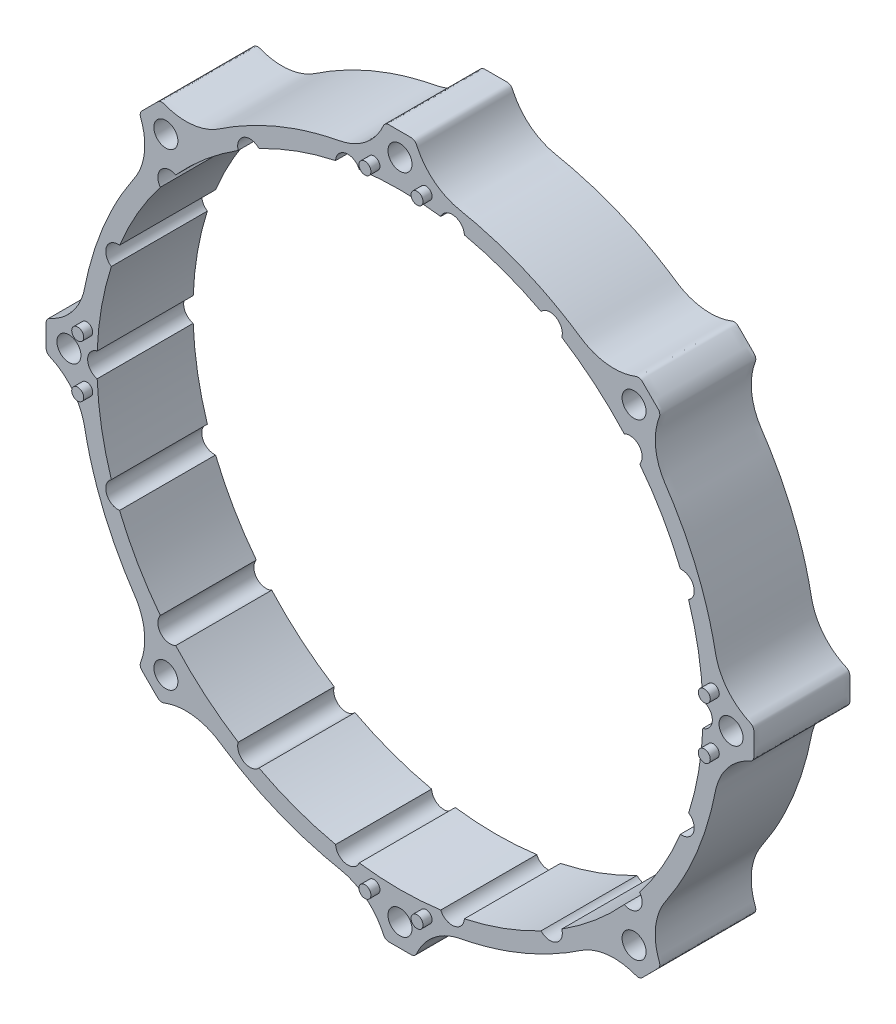
SolidWorks part; units mm, degrees
material "6061-T6 (SS)"
ref_plane "Front Plane" through (0, 0, 0) normal (0, 0, 1) x (1, 0, 0)
ref_plane "Top Plane" through (0, 0, 0) normal (0, 1, 0) x (1, 0, 0)
ref_plane "Right Plane" through (0, 0, 0) normal (1, 0, 0) x (0, 0, -1)
sketch "Sketch1" plane through (0, 0, 0) normal (0, 0, 1) x (1, 0, 0)
  line L0 (0, 0) -> (0, 55.17) construction
  line L1 (0, 0) -> (-8.6824, 49.2404) construction
  arc A0 (-6.7951, 50.0407) -> (-10.7296, 49.347) centre (-8.6824, 49.2404) ccw
  arc A36 (-10.7296, 49.347) -> (-23.5003, 44.6989) centre (0, 0) ccw
  circle A53 centre (0, 0) radius 50 construction
  arc A54 (10.7296, 49.347) -> (6.7951, 50.0407) centre (8.6824, 49.2404) ccw
  arc A55 (26.9602, 42.7012) -> (23.5003, 44.6989) centre (25, 43.3013) ccw
  arc A56 (39.939, 30.9051) -> (37.3709, 33.9656) centre (38.3022, 32.1394) ccw
  arc A57 (48.1006, 15.3814) -> (46.7341, 19.1356) centre (46.9846, 17.101) ccw
  arc A58 (50.4605, -1.9976) -> (50.4605, 1.9976) centre (50, 0) ccw
  arc A59 (46.7341, -19.1356) -> (48.1006, -15.3814) centre (46.9846, -17.101) ccw
  arc A60 (37.3709, -33.9656) -> (39.939, -30.9051) centre (38.3022, -32.1394) ccw
  arc A61 (23.5003, -44.6989) -> (26.9602, -42.7012) centre (25, -43.3013) ccw
  arc A62 (6.7951, -50.0407) -> (10.7296, -49.347) centre (8.6824, -49.2404) ccw
  arc A63 (-10.7296, -49.347) -> (-6.7951, -50.0407) centre (-8.6824, -49.2404) ccw
  arc A64 (-26.9602, -42.7012) -> (-23.5003, -44.6989) centre (-25, -43.3013) ccw
  arc A65 (-39.939, -30.9051) -> (-37.3709, -33.9656) centre (-38.3022, -32.1394) ccw
  arc A66 (-48.1006, -15.3814) -> (-46.7341, -19.1356) centre (-46.9846, -17.101) ccw
  arc A67 (-50.4605, 1.9976) -> (-50.4605, -1.9976) centre (-50, 0) ccw
  arc A68 (-46.7341, 19.1356) -> (-48.1006, 15.3814) centre (-46.9846, 17.101) ccw
  arc A69 (-37.3709, 33.9656) -> (-39.939, 30.9051) centre (-38.3022, 32.1394) ccw
  arc A70 (-23.5003, 44.6989) -> (-26.9602, 42.7012) centre (-25, 43.3013) ccw
  arc A71 (6.7951, 50.0407) -> (-6.7951, 50.0407) centre (0, 0) ccw
  arc A72 (23.5003, 44.6989) -> (10.7296, 49.347) centre (0, 0) ccw
  arc A73 (46.7341, 19.1356) -> (39.939, 30.9051) centre (0, 0) ccw
  arc A74 (37.3709, 33.9656) -> (26.9602, 42.7012) centre (0, 0) ccw
  arc A75 (50.4605, 1.9976) -> (48.1006, 15.3814) centre (0, 0) ccw
  arc A76 (48.1006, -15.3814) -> (50.4605, -1.9976) centre (0, 0) ccw
  arc A77 (39.939, -30.9051) -> (46.7341, -19.1356) centre (0, 0) ccw
  arc A78 (26.9602, -42.7012) -> (37.3709, -33.9656) centre (0, 0) ccw
  arc A79 (10.7296, -49.347) -> (23.5003, -44.6989) centre (0, 0) ccw
  arc A80 (-6.7951, -50.0407) -> (6.7951, -50.0407) centre (0, 0) ccw
  arc A81 (-23.5003, -44.6989) -> (-10.7296, -49.347) centre (0, 0) ccw
  arc A82 (-37.3709, -33.9656) -> (-26.9602, -42.7012) centre (0, 0) ccw
  arc A83 (-46.7341, -19.1356) -> (-39.939, -30.9051) centre (0, 0) ccw
  arc A84 (-50.4605, -1.9976) -> (-48.1006, -15.3814) centre (0, 0) ccw
  arc A85 (-48.1006, 15.3814) -> (-50.4605, 1.9976) centre (0, 0) ccw
  arc A86 (-39.939, 30.9051) -> (-46.7341, 19.1356) centre (0, 0) ccw
  arc A87 (-26.9602, 42.7012) -> (-37.3709, 33.9656) centre (0, 0) ccw
  spline S2 degree 3 number of poles 719 (2.8886, 58.0903) -> (2.8886, 58.0903)
  spline S3 degree 3 number of poles 719 (2.8886, 58.0903) -> (2.8886, 58.0903)
  point P2 (0, 55.17)
  point P30 (-8.6824, 49.2404)
  point P86 (0, 0)
  dimension "D2" = 100
  dimension "D3" = 2.05
  dimension "D5" = 50.5
  dimension "D4" = 10
  dimension "D7" = 55.17
  dimension "D1" = 0
  dimension "D6" = 18
extrude "Boss-Extrude1" add sketch "Sketch1" along normal blind 16
hole_wizard "Ø4.0mm Dowel Hole1" positions "Sketch4" profile "Sketch5" hole size "Ø4.0" standard "ISO" end condition through all
sketch "Sketch4" plane through (0, 0, 0) normal (0, 0, -1) x (-1, 0, 0)
  point P0 (0, 55.17)
sketch "Sketch5" plane through (0, 55.17, 0) normal (1, 0, 0) x (0, 1, 0)
  line L0 (0, 0) -> (0, 16)
  line L1 (0, 16) -> (2, 16)
  line L2 (2, 16) -> (2, 0.025)
  line L3 (2, 0.025) -> (2.025, 0)
  line L5 (2.025, 0) -> (0, 0)
  line L6 (-2, 0.025) -> (-2.025, 0) construction
  line L11 (0, -6.35) -> (0, 107.95) construction
  dimension "Thru Hole Dia." = 4
  dimension "Thru Hole Depth" = 16
  dimension "Near C'Sink Dia." = 4.05
  dimension "Near C'Sink Angle" = 90
pattern_circular "CirPattern1" count 8 over 360 about axis through (0, 0, 0) along (0, 0, 1) of "Ø4.0mm Dowel Hole1"
sketch "Sketch6" plane through (0, 0, 0) normal (0, 0, -1) x (-1, 0, 0)
  line L0 (-8.6824, 49.2404) -> (0, 55.17) construction
  line L1 (0, 55.17) -> (8.6824, 49.2404) construction
  line L2 (8.6824, 49.2404) -> (-8.6824, 49.2404) construction
  point P4 (-4.3412, 52.2052)
  point P7 (4.3412, 52.2052)
hole_wizard "Ø2.0mm Dowel Hole1" positions "Sketch8" profile "Sketch7" hole size "Ø2.0" standard "ISO"
sketch "Sketch8" plane through (0, 0, 0) normal (0, 0, -1) x (-1, 0, 0)
  line L0 (-8.6824, 49.2404) -> (0, 55.17) construction
  point P1 (-4.3412, 52.2052)
  point P5 (4.3412, 52.2052)
sketch "Sketch7" plane through (4.3412, 52.2052, 0) normal (1, 0, 0) x (0, 1, 0)
  line L0 (0, 0) -> (0, 2.3459)
  line L1 (0, 2.3459) -> (1.075, 1.7)
  line L2 (1.075, 1.7) -> (1.075, 0)
  line L5 (1.075, 0) -> (0, 0)
  line L10 (0, 2.3459) -> (-1.075, 1.7) construction
  line L11 (0, -6.35) -> (0, 107.95) construction
  dimension "Hole Dia." = 2.15
  dimension "Hole Depth" = 1.7
  dimension "Drill Angle" = 118
pattern_circular "CirPattern2" count 4 over 360 about axis through (0, 0, 0) along (0, 0, 1) of "Ø2.0mm Dowel Hole1"
sketch "Sketch9" plane through (0, 0, 16) normal (0, 0, 1) x (1, 0, 0)
  line L0 (-8.6824, 49.2404) -> (0, 55.17) construction
  line L1 (0, 55.17) -> (8.6824, 49.2404) construction
  line L2 (8.6824, 49.2404) -> (-8.6824, 49.2404) construction
  circle A0 centre (-4.3412, 52.2052) radius 1
  circle A1 centre (4.3412, 52.2052) radius 1
  dimension "D2" = 2
  dimension "D3" = 2
extrude "Boss-Extrude2" add sketch "Sketch9" along normal blind 1.5
pattern_circular "CirPattern3" count 4 over 360 about axis through (0, 0, 0) along (0, 0, 1) of "Boss-Extrude2"
